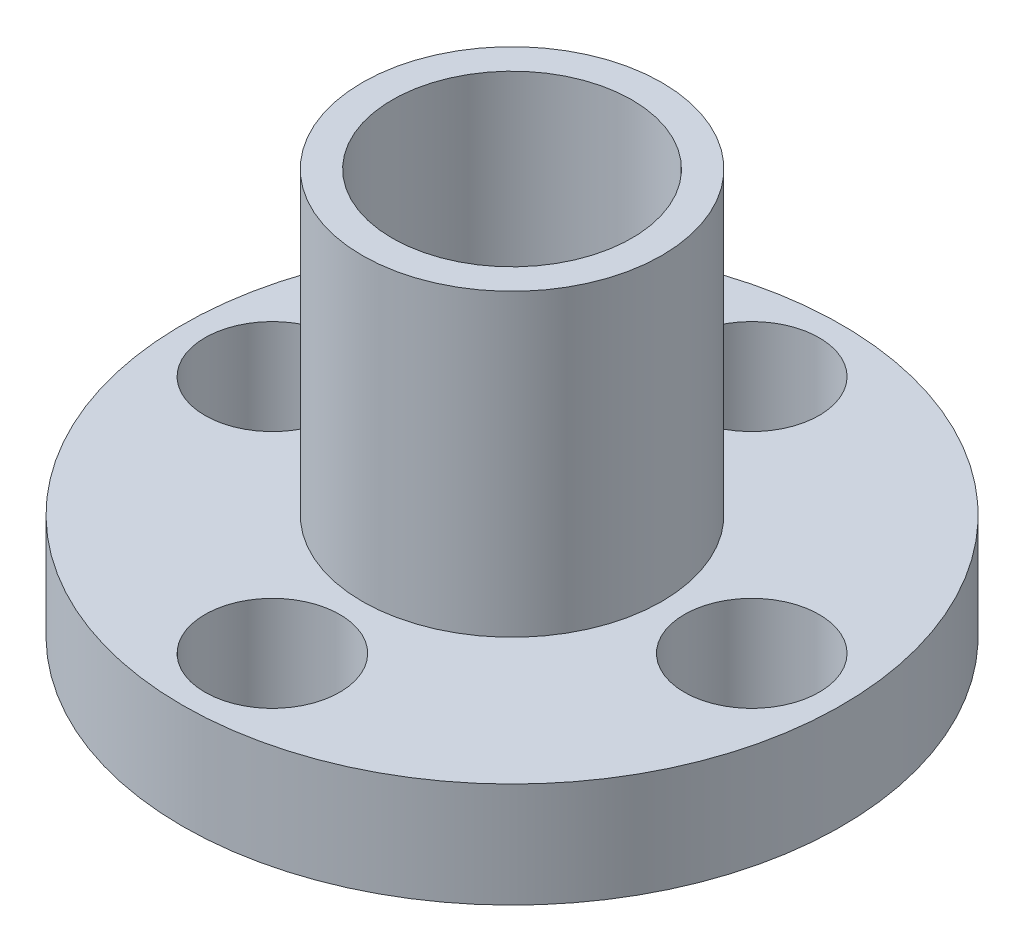
SolidWorks part; units mm, degrees
ref_plane "Front Plane" through (0, 0, 0) normal (0, 0, 1) x (1, 0, 0)
ref_plane "Top Plane" through (0, 0, 0) normal (0, 1, 0) x (1, 0, 0)
ref_plane "Right Plane" through (0, 0, 0) normal (1, 0, 0) x (0, 0, -1)
sketch "Sketch1" plane through (0, 0, 0) normal (0, 1, 0) x (1, 0, 0)
  circle A0 centre (0, 0) radius 11
  circle A1 centre (0, 8) radius 2.25
  circle A2 centre (8, 0) radius 2.25
  circle A3 centre (0, -8) radius 2.25
  circle A4 centre (-8, 0) radius 2.25
  circle A5 centre (0, 0) radius 4
  point P14 (0, 0)
  dimension "D1" = 22
  dimension "D2" = 4.5
  dimension "D5" = 8
  dimension "D3" = 8
  dimension "D4" = 4
extrude "Boss-Extrude1" add sketch "Sketch1" along normal blind 3.5
sketch "Sketch2" plane through (0, 3.5, 0) normal (0, 1, 0) x (1, 0, 0)
  circle A0 centre (0, 0) radius 4
  circle A1 centre (0, 0) radius 5
  dimension "D1" = 10
extrude "Boss-Extrude2" add sketch "Sketch2" along normal blind 10
sketch "Sketch3" plane through (0, 0, 0) normal (0, -1, 0) x (1, 0, 0)
  circle A0 centre (0, 0) radius 4
  circle A1 centre (0, 0) radius 5
  dimension "D1" = 10
extrude "Boss-Extrude3" add sketch "Sketch3" along normal blind 1.5
